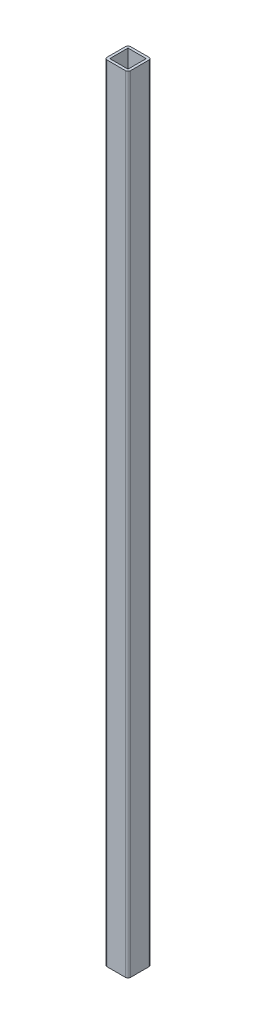
SolidWorks part; units mm, degrees
material "Plain Carbon Steel"
ref_plane "Front Plane" through (0, 0, 0) normal (0, 0, 1) x (1, 0, 0)
ref_plane "Top Plane" through (0, 0, 0) normal (0, 1, 0) x (1, 0, 0)
ref_plane "Right Plane" through (0, 0, 0) normal (1, 0, 0) x (0, 0, -1)
sketch "Sketch1" plane through (0, 0, 0) normal (0, 1, 0) x (1, 0, 0)
  line L1 (2.8, 0) -> (22.8, 0)
  line L2 (0, -2.8) -> (0, -22.8)
  line L3 (2.8, -25.6) -> (22.8, -25.6)
  line L4 (25.6, -2.8) -> (25.6, -22.8)
  arc A0 (22.8, 0) -> (25.6, -2.8) centre (22.8, -2.8) cw
  arc A1 (22.8, -25.6) -> (25.6, -22.8) centre (22.8, -22.8) ccw
  arc A2 (0, -22.8) -> (2.8, -25.6) centre (2.8, -22.8) ccw
  arc A3 (2.8, 0) -> (0, -2.8) centre (2.8, -2.8) ccw
  point P7 (25.6, 0)
  point P10 (25.6, -25.6)
  point P15 (0, 0)
  dimension "D2" = 2.8
  dimension "D1" = 25.6
extrude "Boss-Extrude1" add sketch "Sketch1" along normal blind 861
sketch "Sketch3" plane through (0, 0, 0) normal (0, -1, 0) x (-1, 0, 0)
  line L4 (-2.8, -2.8) -> (-22.8, -2.8)
  line L5 (-2.8, -2.8) -> (-2.8, -22.8)
  line L6 (-2.8, -22.8) -> (-22.8, -22.8)
  line L7 (-22.8, -2.8) -> (-22.8, -22.8)
  line L8 (-2.8, -2.8) -> (-22.8, -22.8) construction
  line L9 (-2.8, -22.8) -> (-22.8, -2.8) construction
  point P6 (-12.8, -12.8)
extrude "Cut-Extrude1" cut sketch "Sketch3" against normal blind 861
